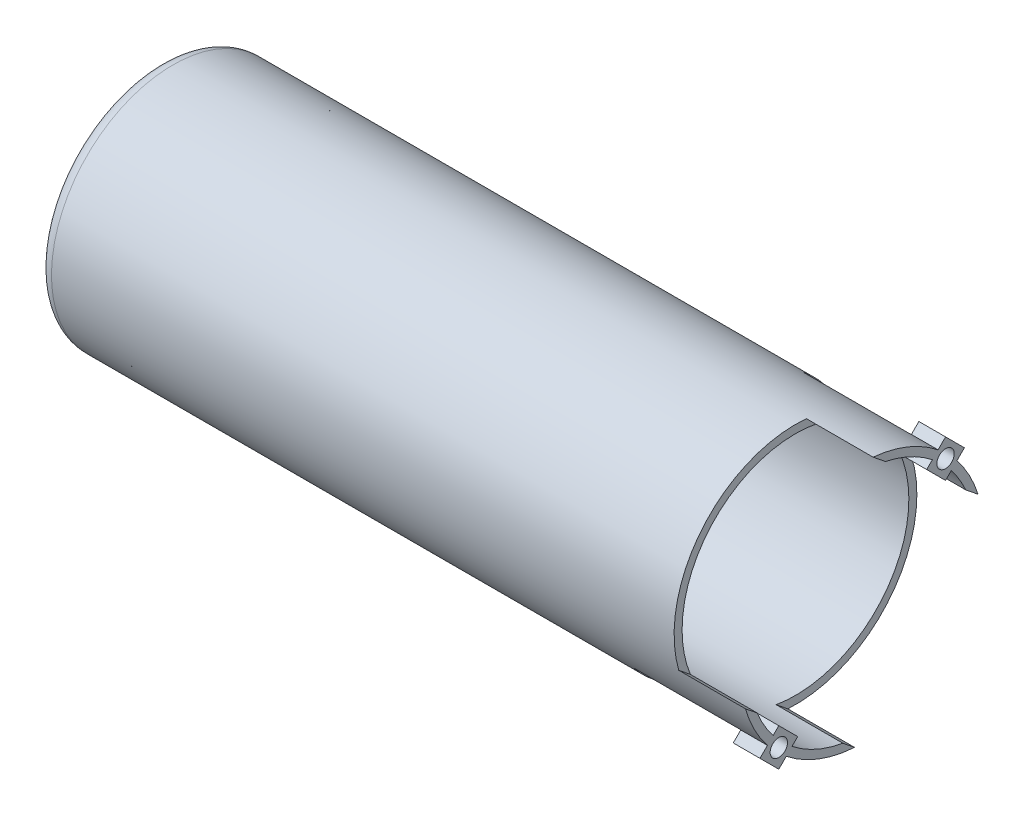
SolidWorks part; units mm, degrees
ref_plane "Front Plane" through (0, 0, 0) normal (0, 0, 1) x (1, 0, 0)
ref_plane "Top Plane" through (0, 0, 0) normal (0, 1, 0) x (1, 0, 0)
ref_plane "Right Plane" through (0, 0, 0) normal (1, 0, 0) x (0, 0, -1)
sketch "Sketch1" plane through (0, 0, 0) normal (0, 0, 1) x (1, 0, 0)
  line L30 (-18.9273, 4.5526) -> (26.9727, 4.5526) construction
  line L39 (-17.3259, -3.9474) -> (34.6741, -3.9474)
  line L40 (34.6741, -3.9474) -> (34.6741, -4.5474)
  line L41 (34.6741, -4.5474) -> (-17.8259, -4.5474)
  line L42 (-17.8259, -4.5474) -> (-18.5312, -0.9474)
  line L43 (-18.5312, -0.9474) -> (-18.5312, 0.0526)
  line L47 (-18.5312, 0.0526) -> (-18.0312, 0.0526)
  line L48 (-18.0312, 0.0526) -> (-17.3259, -3.9474)
  dimension "D4" = 100
  dimension "D1" = 4.5
  dimension "D3" = 8.5
  dimension "D5" = 52
  dimension "D6" = 52.5
  dimension "D7" = 0.5
  dimension "D22" = 0.6
  dimension "D26" = 1
revolve "Revolve1" add sketch "Sketch1" angle 360 about L30
ref_plane "Plane1" through (-18.5312, 0, 0) normal (-1, 0, 0) x (0, 0, 1)
sketch "Sketch3" plane through (-18.5312, 0, 0) normal (-1, 0, 0) x (0, 0, 1)
  line L0 (-10.6704, 4.5526) -> (11.0485, 4.5526) construction
  circle A0 centre (0, 4.5526) radius 5.5
  circle A1 centre (0, 4.5526) radius 4.5 construction
  dimension "D1" = 11
  dimension "D2" = 0
  dimension "D3" = 0
fillet "Fillet1" radius 1 1 edges at (-17.8259, 4.5526, 9.1)
extrude "Cut-Extrude1" cut sketch "Sketch3" against normal blind 0.35
ref_plane "Plane2" through (34.6741, 0, 0) normal (1, 0, 0) x (0, 0, -1)
sketch "Sketch5" plane through (34.6741, 0, 0) normal (1, 0, 0) x (0, 0, -1)
  line L0 (0, -6.1653) -> (0, 15.5545) construction
  line L5 (-13.0271, 4.5526) -> (16.6492, 4.5526) construction
  line L6 (0, 0.0526) -> (-4.5929, 0.0526) construction
  circle A0 centre (6.25, 10.8026) radius 0.65
  circle A1 centre (-6.25, -1.6974) radius 0.65
  circle A2 centre (0, 4.5526) radius 4.5 construction
  dimension "D3" = 1.3
  dimension "D4" = 1.3
  dimension "D6" = 4.5
  dimension "D1" = 12.5
  dimension "D2" = 12.5
  dimension "D5" = 6.25
  dimension "D7" = 6.25
sketch "Sketch4" plane through (34.6741, 0, 0) normal (1, 0, 0) x (0, 0, -1)
  line L0 (0, -7.0957) -> (0, 15.0957) construction
  line L5 (0, 4) -> (-16.5111, 4) construction
  line L6 (-13.6281, 5.9952) -> (5.0563, -9.0677)
  line L7 (-13.6281, 5.9952) -> (-4.2138, 17.673)
  line L8 (5.0563, -9.0677) -> (14.4707, 2.61)
  line L9 (-4.2138, 17.673) -> (14.4707, 2.61)
  dimension "D1" = 15
  dimension "D2" = 24
  dimension "D3" = 7
  dimension "D5" = 4
extrude "Cut-Extrude2" cut sketch "Sketch4" against normal blind 5
sketch "Sketch6" plane through (34.6741, 0, 0) normal (1, 0, 0) x (0, 0, -1)
  line L8 (-6.25, -0.2832) -> (-4.8358, -1.6974)
  line L9 (-4.8358, -1.6974) -> (-6.25, -3.1116)
  line L10 (-6.25, -3.1116) -> (-7.6642, -1.6974)
  line L11 (-7.6642, -1.6974) -> (-6.25, -0.2832)
  line L12 (4.8358, 10.8026) -> (6.25, 12.2168)
  line L13 (6.25, 12.2168) -> (7.6642, 10.8026)
  line L14 (7.6642, 10.8026) -> (6.25, 9.3884)
  line L15 (6.25, 9.3884) -> (4.8358, 10.8026)
  dimension "D1" = 2
  dimension "D2" = 2
  dimension "D3" = 1
  dimension "D4" = 1
  dimension "D5" = 2
  dimension "D6" = 2
  dimension "D7" = 1
  dimension "D8" = 1
extrude "Boss-Extrude2" add sketch "Sketch6" against normal blind 2
extrude "Cut-Extrude3" cut sketch "Sketch5" against normal blind 5
ref_plane "Plane3" through (32.6741, 0, 0) normal (-1, 0, 0) x (0, 0, 1)
sketch "Sketch7" plane through (32.6741, 0, 0) normal (-1, 0, 0) x (0, 0, 1)
  circle A0 centre (6.25, -1.6974) radius 1.1
  circle A1 centre (-6.25, 10.8026) radius 1.1
  dimension "D1" = 2.2
  dimension "D2" = 2.2
extrude "Cut-Extrude4" cut sketch "Sketch7" along normal blind 8
